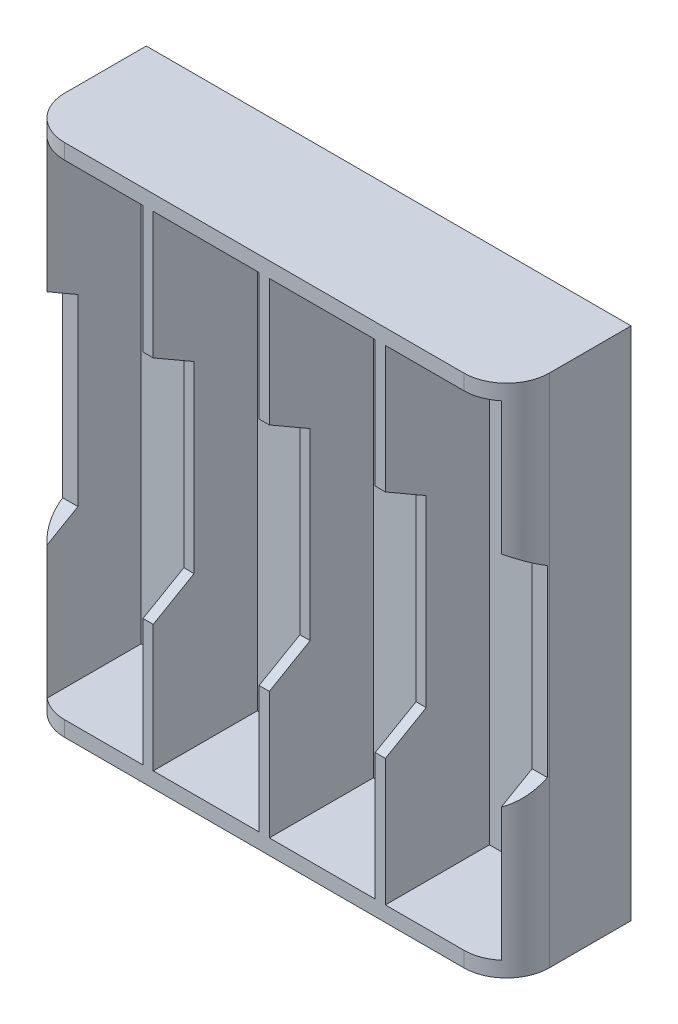
SolidWorks part; units mm, degrees
ref_plane "Front" through (0, 0, 0) normal (0, 0, 1) x (1, 0, 0)
ref_plane "Top" through (0, 0, 0) normal (0, 1, 0) x (1, 0, 0)
ref_plane "Right" through (0, 0, 0) normal (1, 0, 0) x (0, 0, -1)
sketch "Sketch1" plane through (0, 0, 0) normal (0, 0, 1) x (1, 0, 0)
  line L1 (-23.76, -25.25) -> (23.76, -25.25)
  line L2 (-23.76, -25.25) -> (-23.76, 25.25)
  line L3 (-23.76, 25.25) -> (23.76, 25.25)
  line L4 (23.76, -25.25) -> (23.76, 25.25)
  line L5 (-23.76, -25.25) -> (23.76, 25.25) construction
  line L6 (-23.76, 25.25) -> (23.76, -25.25) construction
  point P0 (0, 0)
  dimension "D1" = 50.5
  dimension "D2" = 47.52
extrude "Boss-Extrude1" add sketch "Sketch1" along normal blind 2
sketch "Sketch2" plane through (0, -25.25, 0) normal (0, -1, 0) x (1, 0, 0)
  line L0 (-19.56, 12.2) -> (19.56, 12.2)
  line L1 (0, 0) -> (0, 12.2) construction
  line L2 (-23.76, 0) -> (23.76, 0) construction
  line L3 (-23.76, 2) -> (-23.76, 8)
  line L4 (-23.76, 2) -> (23.76, 2)
  line L5 (-23.76, 2) -> (23.76, 2) construction
  line L6 (23.76, 2) -> (23.76, 8)
  arc A0 (-23.76, 8) -> (-19.56, 12.2) centre (-19.56, 8) cw
  arc A1 (23.76, 8) -> (19.56, 12.2) centre (19.56, 8) ccw
  point P17 (0, 2)
  dimension "D1" = 12.2
  dimension "D2" = 8
extrude "Boss-Extrude2" add sketch "Sketch2" against normal up to surface (50.5 mm away) up to face at (0, 25.25, 1)
sketch "Sketch3" plane through (0, 0, 12.2) normal (0, 0, 1) x (1, 0, 0)
  line L1 (0, 0) -> (0, -25.25) construction
  line L2 (-22.26, 23.75) -> (-11.88, 23.75)
  line L3 (-22.26, 23.75) -> (-22.26, -23.75)
  line L4 (-22.26, -23.75) -> (-11.88, -23.75)
  line L5 (-11.88, 23.75) -> (-11.88, -23.75)
  line L6 (-10.88, 23.75) -> (-0.5, 23.75)
  line L7 (-10.88, 23.75) -> (-10.88, -23.75)
  line L9 (-10.88, -23.75) -> (-0.5, -23.75)
  line L10 (-0.5, 23.75) -> (-0.5, -23.75)
  line L11 (19.56, -25.25) -> (-19.56, -25.25) construction
  line L12 (-19.56, 25.25) -> (19.56, 25.25) construction
  line L13 (-23.76, 25.25) -> (-23.76, -25.25) construction
  line L14 (0.5, 23.75) -> (0.5, -23.75)
  line L15 (10.88, -23.75) -> (0.5, -23.75)
  line L16 (10.88, 23.75) -> (10.88, -23.75)
  line L17 (10.88, 23.75) -> (0.5, 23.75)
  line L18 (11.88, 23.75) -> (11.88, -23.75)
  line L19 (22.26, -23.75) -> (11.88, -23.75)
  line L20 (22.26, 23.75) -> (22.26, -23.75)
  line L21 (22.26, 23.75) -> (11.88, 23.75)
  point P15 (-1.9341, 23.75)
  dimension "D1" = 1.5
  dimension "D2" = 1.5
  dimension "D3" = 0.5
  dimension "D4" = 1
  dimension "D5" = 1.5
extrude "Cut-Extrude1" cut sketch "Sketch3" against normal offset from surface (10.2 mm away) 2 up to face at (0, 0, 0)
sketch "Sketch4" plane through (0, 0, 0) normal (1, 0, 0) x (0, 0, -1)
  line L0 (0, 0) -> (-17.2, 0) construction
  line L1 (-17.2, -14.1962) -> (-17.2, 14.1962)
  line L2 (-17.2, 14.1962) -> (-8.2, 9)
  line L3 (-8.2, 9) -> (-8.2, -9)
  line L4 (-17.2, -14.1962) -> (-8.2, -9)
  line L5 (0, -25.25) -> (0, 25.25) construction
  line L6 (-12.2, 25.25) -> (-12.2, 23.75) construction
  point P7 (-8.2, 0)
  dimension "D1" = 8.2
  dimension "D2" = 18
  dimension "D3" = 60
  dimension "D4" = 5
extrude "Cut-Extrude2" cut sketch "Sketch4" against normal through all both and the other way through all
